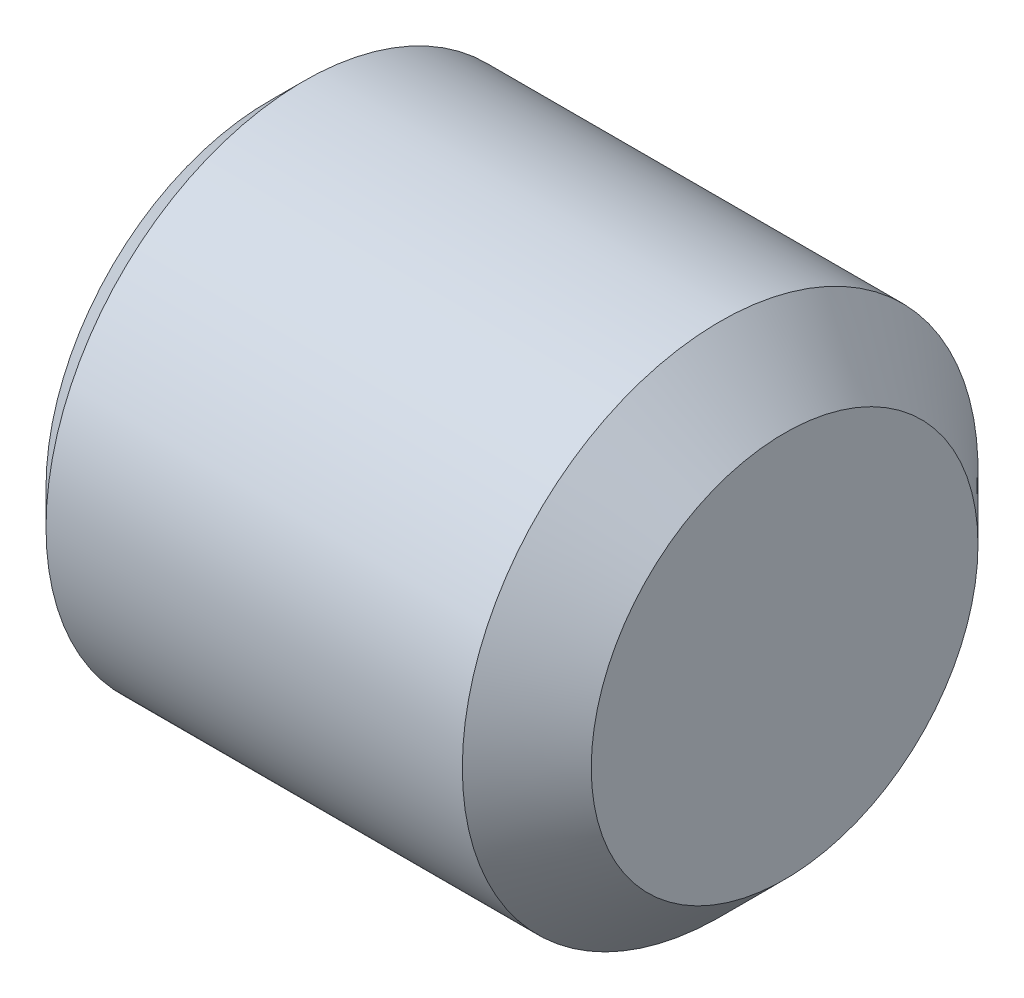
SolidWorks part; units mm, degrees
ref_plane "Front" through (0, 0, 0) normal (0, 0, 1) x (1, 0, 0)
ref_plane "Top" through (0, 0, 0) normal (0, 1, 0) x (1, 0, 0)
ref_plane "Right" through (0, 0, 0) normal (1, 0, 0) x (0, 0, -1)
other "Configuration Table"
sketch "Sketch1" plane through (0, 0, 0) normal (0, 0, 1) x (1, 0, 0)
  line L0 (0, 0) -> (20, 0)
  line L1 (20, 0) -> (20, 7.5)
  line L2 (20, 7.5) -> (17.5, 10)
  line L3 (17.5, 10) -> (1.353, 10)
  line L4 (1.353, 10) -> (0, 8.647)
  line L5 (0, 8.647) -> (0, 0)
  line L6 (-10.745, 0) -> (0.8952, 0) construction
  dimension "df" = 4.134
  dimension "D2" = 45
  dimension "D1" = 45
revolve "Base" add sketch "Sketch1" angle 360 about L6
cosmetic thread "ThreadCosmetic1" [suppressed]
sketch "Sketch2" plane through (0, -0.0219, 0.0101) normal (-1, 0, 0) x (0, 0, 1)
  line L1 (5.7634, 0.0219) -> (2.8766, 5.0219)
  line L2 (2.8766, 5.0219) -> (-2.8969, 5.0219)
  line L3 (-2.8969, 5.0219) -> (-5.7836, 0.0219)
  line L4 (-5.7836, 0.0219) -> (-2.8969, -4.9781)
  line L5 (-2.8969, -4.9781) -> (2.8766, -4.9781)
  line L6 (2.8766, -4.9781) -> (5.7634, 0.0219)
  circle A0 centre (-0.0101, 0.0219) radius 5 construction
  dimension "s" = 10
extrude "HexagonSocket" cut sketch "Sketch2" against normal blind 8
sketch "Sketch3" plane through (0, 0, 0) normal (0, 0, 1) x (1, 0, 0)
  line L0 (-3.1441, 0) -> (0.1622, 0) construction
  line L2 (8, 5) -> (10.8868, 0)
  line L4 (8, 5) -> (8, 0)
  line L5 (8, 0) -> (10.8868, 0)
  dimension "D1" = 60
revolve "Cut-Revolve1" cut sketch "Sketch3" angle 360 about L0
sketch "Sketch4" plane through (0, 0, 0) normal (0, 0, 1) x (1, 0, 0)
  line L0 (1.353, 8.8283) -> (2.0295, 10)
  line L1 (2.0295, 10) -> (2.0295, 11.353)
  line L2 (2.0295, 11.353) -> (0.6765, 11.353)
  line L3 (0.6765, 11.353) -> (0.6765, 10)
  line L4 (0.6765, 10) -> (1.353, 8.8283)
  line L5 (0, 0) -> (0.9616, 0) construction
  line L6 (1.353, 10) -> (1.353, -10) construction
  dimension "D1" = 5
  dimension "D2" = 0.433
revolve "Cut-Revolve10" [suppressed] cut sketch "Sketch4" angle 360 about L5
pattern_linear "LPattern10" [suppressed] count 47 spacing 0.5196 along (1, 0, 0)
equation "\"df@Sketch1\" = \"D2@ThreadCosmetic1\""
equation "\"D1@Sketch4\" = \"d@Sketch1\""
equation "\"D2@Sketch4\" =  ( \"d@Sketch1\" - \"D2@ThreadCosmetic1\" )  / 2"
equation "\"D3@LPattern10\" = \"D2@Sketch4\" * 1.2"
equation "\"D1@LPattern10\" = (  \"l@Sketch1\" -  ( \"d@Sketch1\" - \"df@Sketch1\" )  / 2 )  / \"D3@LPattern10\""
